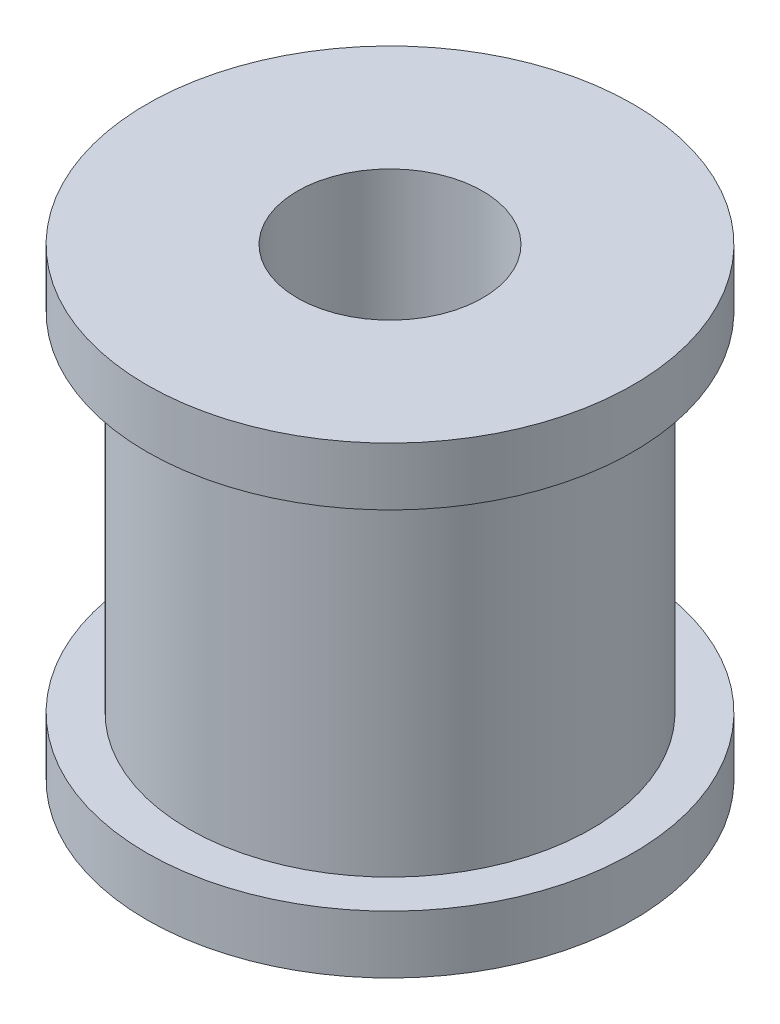
SolidWorks part; units mm, degrees
ref_plane "Piano frontale" through (0, 0, 0) normal (0, 0, 1) x (1, 0, 0)
ref_plane "Piano superiore" through (0, 0, 0) normal (0, 1, 0) x (1, 0, 0)
ref_plane "Piano destro" through (0, 0, 0) normal (1, 0, 0) x (0, 0, -1)
sketch "Schizzo1" plane through (0, 0, 0) normal (0, 0, 1) x (1, 0, 0)
  line L0 (0, 12.3387) -> (0, -16.129) construction
  line L1 (4, -7.6613) -> (10.5, -7.6613)
  line L2 (10.5, -7.6613) -> (10.5, -5.1613)
  line L3 (10.5, -5.1613) -> (8.7, -5.1613)
  line L4 (8.7, -5.1613) -> (8.7, 9.8387)
  line L5 (8.7, 9.8387) -> (10.5, 9.8387)
  line L6 (10.5, 9.8387) -> (10.5, 12.3387)
  line L7 (10.5, 12.3387) -> (4, 12.3387)
  line L8 (4, 12.3387) -> (4, -7.6613)
  dimension "D1" = 20
  dimension "D2" = 15
  dimension "D3" = 4
  dimension "D4" = 10.5
  dimension "D5" = 8.7
revolve "Rivoluzione1" add sketch "Schizzo1" angle 360 about L0
